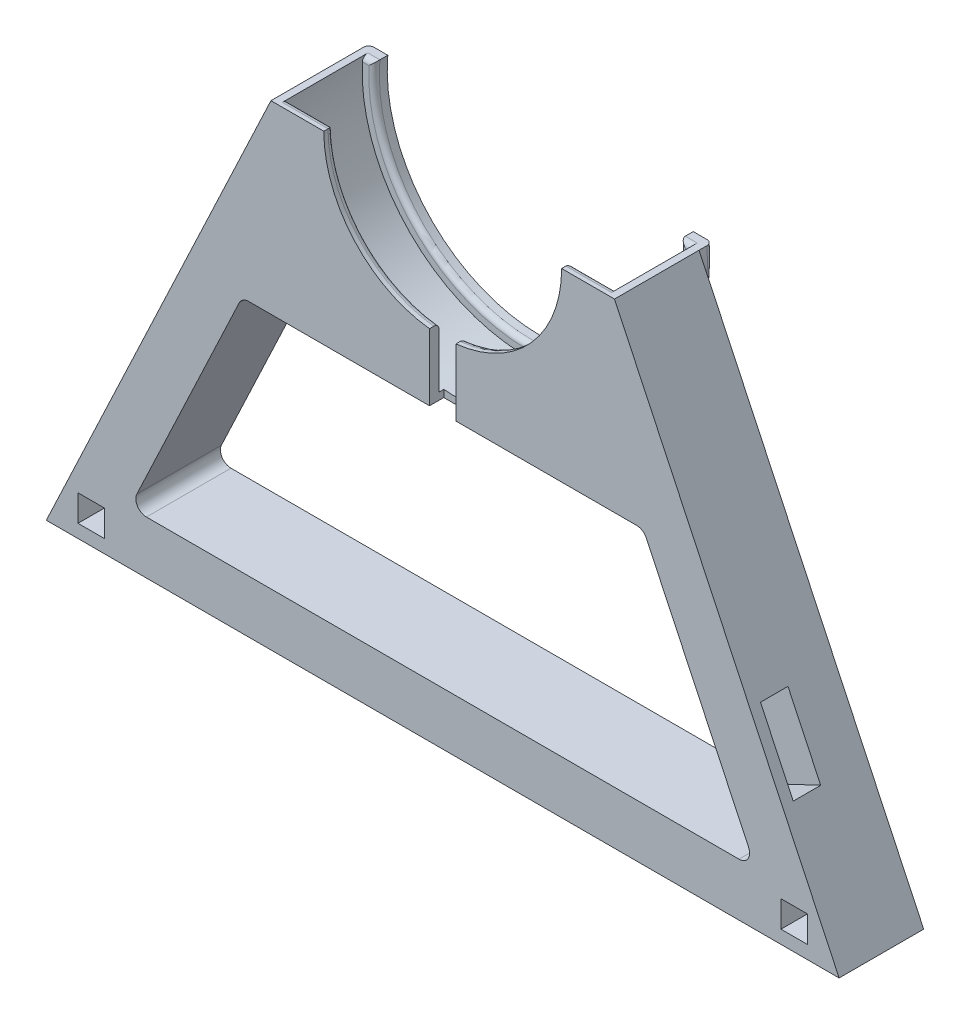
SolidWorks part; units mm, degrees
ref_plane "Front Plane" through (0, 0, 0) normal (0, 0, 1) x (1, 0, 0)
ref_plane "Top Plane" through (0, 0, 0) normal (0, 1, 0) x (1, 0, 0)
ref_plane "Right Plane" through (0, 0, 0) normal (1, 0, 0) x (0, 0, -1)
sketch "Sketch1" plane through (0, 0, 0) normal (0, 0, 1) x (1, 0, 0)
  line L0 (-75, 0) -> (75, 0)
  line L1 (75, 0) -> (32.5, 90)
  line L2 (32.5, 90) -> (-32.5, 90)
  line L3 (-32.5, 90) -> (-75, 0)
  line L4 (-59.2189, 10) -> (-37.9689, 55)
  line L5 (-37.9689, 55) -> (37.9689, 55)
  line L6 (37.9689, 55) -> (59.2189, 10)
  line L7 (59.2189, 10) -> (-59.2189, 10)
  dimension "D2" = 150
  dimension "D3" = 90
  dimension "D4" = 0
  dimension "D5" = 32.5
  dimension "D6" = 75
  dimension "D7" = 10
  dimension "D8" = 10
  dimension "D9" = 10
  dimension "D10" = 35
  dimension "D11" = 65
extrude "Boss-Extrude1" add sketch "Sketch1" along normal blind 16
sketch "Sketch2" plane through (0, 0, 0) normal (0, 0, -1) x (-1, 0, 0)
  line L2 (-32.5, 90) -> (32.5, 90) construction
  circle A0 centre (0, 87.5) radius 31.25
  dimension "D1" = 62.5
  dimension "D2" = 0
  dimension "D3" = 2.5
extrude "Cut-Extrude1" cut sketch "Sketch2" against normal blind 14.2
sketch "Sketch3" plane through (0, 0, 14.2) normal (0, 0, -1) x (-1, 0, 0)
  line L0 (31.1498, 90) -> (-31.1498, 90) construction
  circle A0 centre (0, 90) radius 22.5
  dimension "D1" = 45
extrude "Cut-Extrude2" cut sketch "Sketch3" against normal blind 14.2
fillet "Fillet1" radius 2 4 edges at (59.2189, 10, 8) (-59.2189, 10, 8) (37.9689, 55, 8) (-37.9689, 55, 8)
sketch "Sketch4" plane through (61.3249, 28.959, 0) normal (0.9042, 0.427, 0) x (0, 0, -1)
  line L0 (-16, 67.5047) -> (0, 67.5047) construction
  line L1 (-14, -6.9953) -> (-8.8, -6.9953)
  line L2 (-14, -6.9953) -> (-14, 7.5047)
  line L3 (-14, 7.5047) -> (-8.8, 7.5047)
  line L4 (-8.8, -6.9953) -> (-8.8, 7.5047)
  line L5 (-16, -32.0255) -> (-16, 67.5047) construction
  point P4 (-11.4, 7.5047)
  dimension "D1" = 5.2
  dimension "D2" = 14.5
  dimension "D3" = 60
  dimension "D4" = 2
extrude "Cut-Extrude3" cut sketch "Sketch4" against normal blind 10
sketch "Sketch5" plane through (0, 0, 0) normal (0, 0, -1) x (-1, 0, 0)
  line L1 (75, 0) -> (-75, 0) construction
  line L2 (-69, 7.5) -> (-64, 7.5)
  line L3 (-69, 7.5) -> (-69, 2.5)
  line L4 (-69, 2.5) -> (-64, 2.5)
  line L5 (-64, 7.5) -> (-64, 2.5)
  line L7 (64, 7.5) -> (69, 7.5)
  line L8 (64, 7.5) -> (64, 2.5)
  line L9 (64, 2.5) -> (69, 2.5)
  line L10 (69, 7.5) -> (69, 2.5)
  dimension "D1" = 5
  dimension "D4" = 2.5
  dimension "D2" = 5
  dimension "D3" = 6
  dimension "D5" = 5
  dimension "D6" = 5
  dimension "D7" = 2.5
  dimension "D8" = 6
extrude "Cut-Extrude4" cut sketch "Sketch5" against normal through all
sketch "Sketch6" plane through (0, 0, 16) normal (0, 0, 1) x (1, 0, 0)
  line L0 (36.7015, 55) -> (-36.7015, 55) construction
  line L1 (-2.5, 55) -> (2.5, 55)
  line L2 (-2.5, 55) -> (-2.5, 70)
  line L3 (-2.5, 70) -> (2.5, 70)
  line L4 (2.5, 55) -> (2.5, 70)
  line L5 (-75, 0) -> (75, 0) construction
  point P8 (0, 0)
  dimension "D1" = 5
  dimension "D2" = 0
  dimension "D3" = 2.5
  dimension "D4" = 15
extrude "Cut-Extrude5" cut sketch "Sketch6" against normal blind 2.7
sketch "Sketch7" plane through (0, 0, 0) normal (0, 0, -1) x (-1, 0, 0)
  line L1 (32.5, 90) -> (75, 0) construction
  line L3 (-32.5, 90) -> (-28.892, 90)
  line L4 (28.892, 90) -> (32.5, 90)
  arc A0 (-32.5, 90) -> (32.5, 90) centre (0, 87.5) ccw
  arc A1 (28.892, 90) -> (-28.892, 90) centre (0, 87.5) cw
extrude "Boss-Extrude2" add sketch "Sketch7" along normal blind 2.5
fillet "Fillet2" radius 1 1 edges at (0, 54.904, -2.5)
fillet "Fillet3" radius 1 7 edges at (-30.0209, 90, 0) (30.0209, 90, 0) (0, 58.5, 0) (-26.8249, 90, 14.2) (26.8249, 90, 14.2) (16.7705, 75, 14.2) (-16.7705, 75, 14.2)
